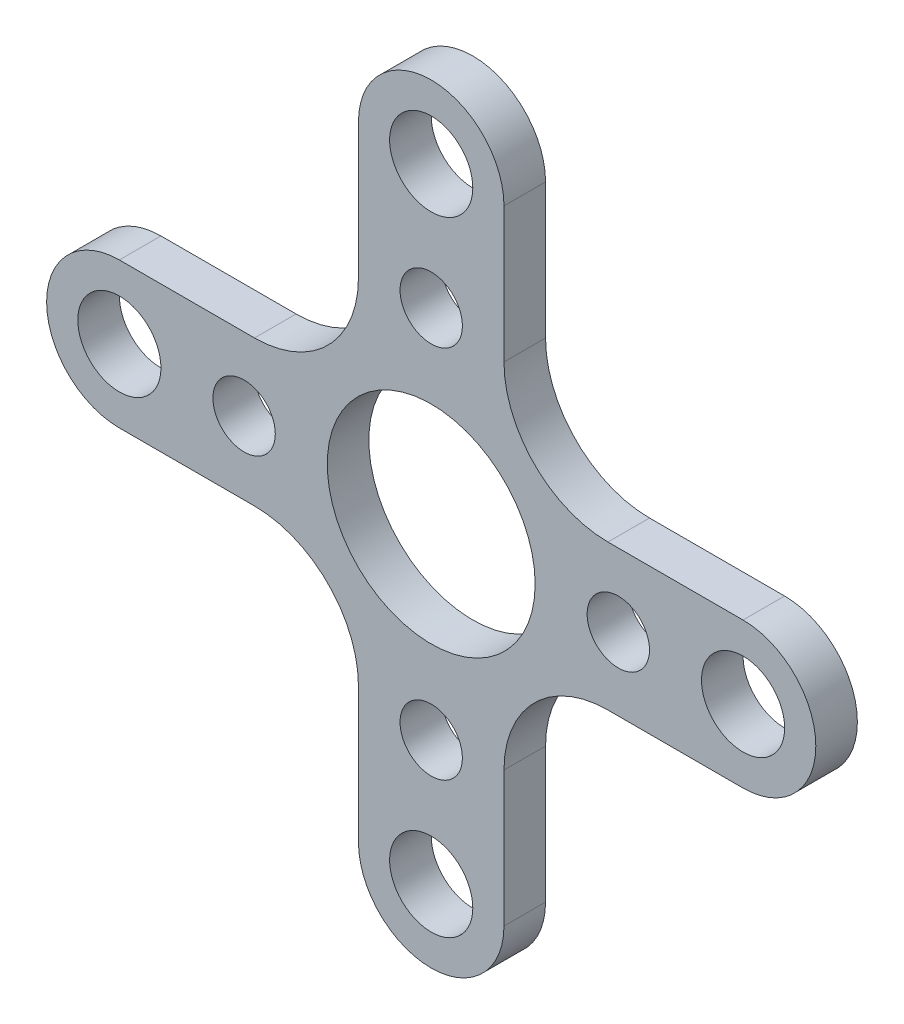
SolidWorks part; units mm, degrees
ref_plane "Plan de face" through (0, 0, 0) normal (0, 0, 1) x (1, 0, 0)
ref_plane "Plan de dessus" through (0, 0, 0) normal (0, 1, 0) x (1, 0, 0)
ref_plane "Plan de droite" through (0, 0, 0) normal (1, 0, 0) x (0, 0, -1)
sketch "Esquisse1" plane through (0, 0, 0) normal (0, 0, 1) x (1, 0, 0)
  line L0 (18, -6.5) -> (18, -13)
  line L1 (6.5, -1.5) -> (13, -1.5)
  line L3 (6.5, 5.5) -> (13, 5.5)
  line L6 (18, 17) -> (18, 10.5)
  line L8 (25, 17) -> (25, 10.5)
  line L9 (30, 5.5) -> (36.5, 5.5)
  line L10 (25, -6.5) -> (25, -13)
  line L11 (30, -1.5) -> (36.5, -1.5)
  arc A0 (30, 5.5) -> (25, 10.5) centre (30, 10.5) cw
  arc A1 (25, -6.5) -> (30, -1.5) centre (30, -6.5) cw
  arc A2 (18, -6.5) -> (13, -1.5) centre (13, -6.5) ccw
  arc A3 (18, 10.5) -> (13, 5.5) centre (13, 10.5) cw
  arc A4 (6.5, -1.5) -> (6.5, 5.5) centre (6.5, 2) cw
  arc A5 (18, 17) -> (25, 17) centre (21.5, 17) cw
  arc A6 (36.5, 5.5) -> (36.5, -1.5) centre (36.5, 2) cw
  arc A7 (25, -13) -> (18, -13) centre (21.5, -13) cw
  circle A8 centre (21.5, 2) radius 5
  circle A9 centre (12.5, 2) radius 1.5
  circle A10 centre (6.5, 2) radius 2
  circle A11 centre (21.5, 17) radius 2
  circle A12 centre (21.5, 11) radius 1.5
  circle A13 centre (36.5, 2) radius 2
  circle A14 centre (30.5, 2) radius 1.5
  circle A15 centre (21.5, -13) radius 2
  circle A16 centre (21.5, -7) radius 1.5
  point P17 (25, -1.5)
  point P25 (21.5, 2)
  point P38 (21.5, 2)
  point P48 (21.5, 2)
  dimension "D7" = 5
  dimension "D2" = 10
  dimension "D3" = 3
  dimension "D6" = 4
  dimension "D9" = 30
  dimension "D10" = 3.5
  dimension "D16" = 3.5
  dimension "D17" = 3.5
  dimension "D18" = 3.5
  dimension "D4" = 6
  dimension "D5" = 3.5
  dimension "D8" = 4
  dimension "D12" = 7
  dimension "D13" = 7
  dimension "D14" = 7
  dimension "D15" = 7
  dimension "D19" = 0
  dimension "D11" = 4
extrude "Boss.-Extru.1" add sketch "Esquisse1" along normal blind 2
